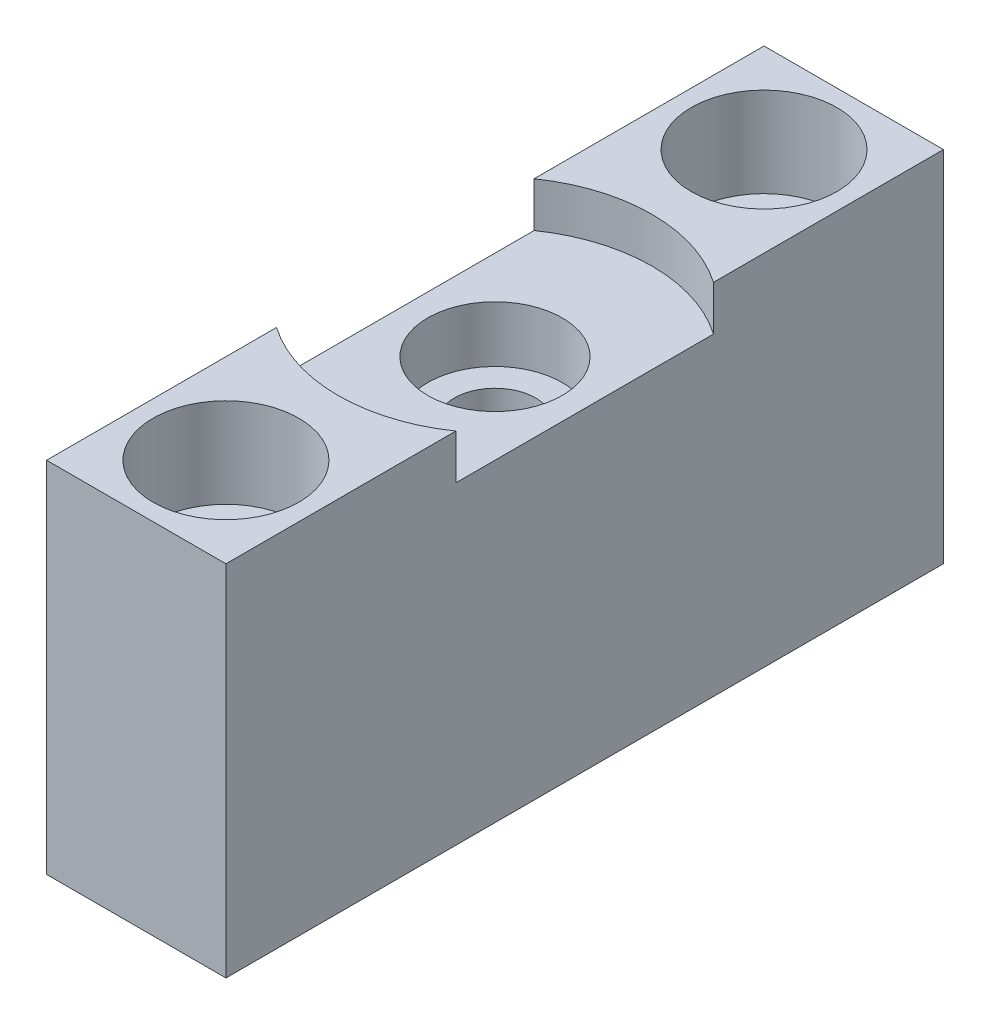
SolidWorks part; units mm, degrees
ref_plane "Front Plane" through (0, 0, 0) normal (0, 0, 1) x (1, 0, 0)
ref_plane "Top Plane" through (0, 0, 0) normal (0, 1, 0) x (1, 0, 0)
ref_plane "Right Plane" through (0, 0, 0) normal (1, 0, 0) x (0, 0, -1)
sketch "Sketch1" plane through (0, 0, 0) normal (1, 0, 0) x (0, 0, -1)
  line L1 (0, 0) -> (101.6, 0)
  line L2 (0, 0) -> (0, 50.8)
  line L3 (0, 50.8) -> (101.6, 50.8)
  line L4 (101.6, 0) -> (101.6, 50.8)
  dimension "D1" = 101.6
  dimension "D2" = 50.8
extrude "Boss-Extrude1" add sketch "Sketch1" along normal blind 25.4
sketch "Sketch2" plane through (0, 50.8, 0) normal (0, 1, 0) x (1, 0, 0)
  line L0 (0, 50.8) -> (25.4, 50.8) construction
  line L1 (0, 101.6) -> (0, 0) construction
  line L2 (25.4, 101.6) -> (25.4, 0) construction
  circle A0 centre (12.7, 50.8) radius 22.225
  dimension "D1" = 44.45
extrude "Cut-Extrude1" cut sketch "Sketch2" against normal blind 6.35
sketch "Sketch3" plane through (0, 44.45, 0) normal (0, 1, 0) x (1, 0, 0)
  circle A0 centre (12.7, 50.8) radius 9.525
  arc A1 (25.4, 69.039) -> (0, 69.039) centre (12.7, 50.8) ccw construction
  dimension "D1" = 19.05
extrude "Cut-Extrude2" cut sketch "Sketch3" against normal blind 7.9375
hole_wizard "1/2-20 Tapped Hole1" positions "Sketch4" profile "Sketch5" tap size "1/2-20" standard "ANSI Inch" end condition through all
sketch "Sketch4" plane through (0, 36.5125, 0) normal (0, 1, 0) x (1, 0, 0)
  circle A0 centre (12.7, 50.8) radius 9.525 construction
  point P0 (12.7, 50.8)
  point P3 (0, 0)
sketch "Sketch5" plane through (12.7, 36.5125, -50.8) normal (1, 0, 0) x (0, 0, 1)
  line L0 (0, 0) -> (0, 36.5125)
  line L1 (0, 36.5125) -> (5.7544, 36.5125)
  line L2 (5.7544, 36.5125) -> (5.7544, 0)
  line L5 (5.7544, 0) -> (0, 0)
  line L11 (0, -6.35) -> (0, 107.95) construction
  dimension "Thru Tap Drill Dia." = 11.5087
  dimension "Thru Tap Drill Depth" = 36.5125
cosmetic thread "Hole Thread1" parameters "D2"=12.7
hole_wizard "CBORE for 1/2 Socket Head Cap Screw1" positions "Sketch6" profile "Sketch7" counterbore size "1/2" standard "ANSI Inch" end condition through all
sketch "Sketch6" plane through (0, 50.8, 0) normal (0, 1, 0) x (1, 0, 0)
  line L0 (12.7, 101.6) -> (12.7, 0) construction
  line L1 (25.4, 101.6) -> (0, 101.6) construction
  line L2 (25.4, 0) -> (0, 0) construction
  line L3 (0, 50.8) -> (25.4, 50.8) construction
  line L4 (0, 32.561) -> (0, 69.039) construction
  line L5 (25.4, 32.561) -> (25.4, 69.039) construction
  point P0 (12.7, 88.9)
  point P2 (12.7, 12.7)
  dimension "D1" = 76.2
  dimension "D2" = 38.1
sketch "Sketch7" plane through (12.7, 50.8, -88.9) normal (1, 0, 0) x (0, 0, 1)
  line L0 (0, 0) -> (0, 50.8)
  line L1 (0, 50.8) -> (6.7462, 50.8)
  line L3 (6.7462, 50.8) -> (6.7462, 12.7)
  line L4 (6.7462, 12.7) -> (10.3187, 12.7)
  line L5 (10.3187, 12.7) -> (10.3187, 0)
  line L7 (10.3187, 0) -> (0, 0)
  line L11 (0, -6.35) -> (0, 107.95) construction
  dimension "Thru Hole Dia." = 13.4925
  dimension "Thru Hole Depth" = 50.8
  dimension "C'Bore Dia." = 20.6375
  dimension "C'Bore Depth" = 12.7
